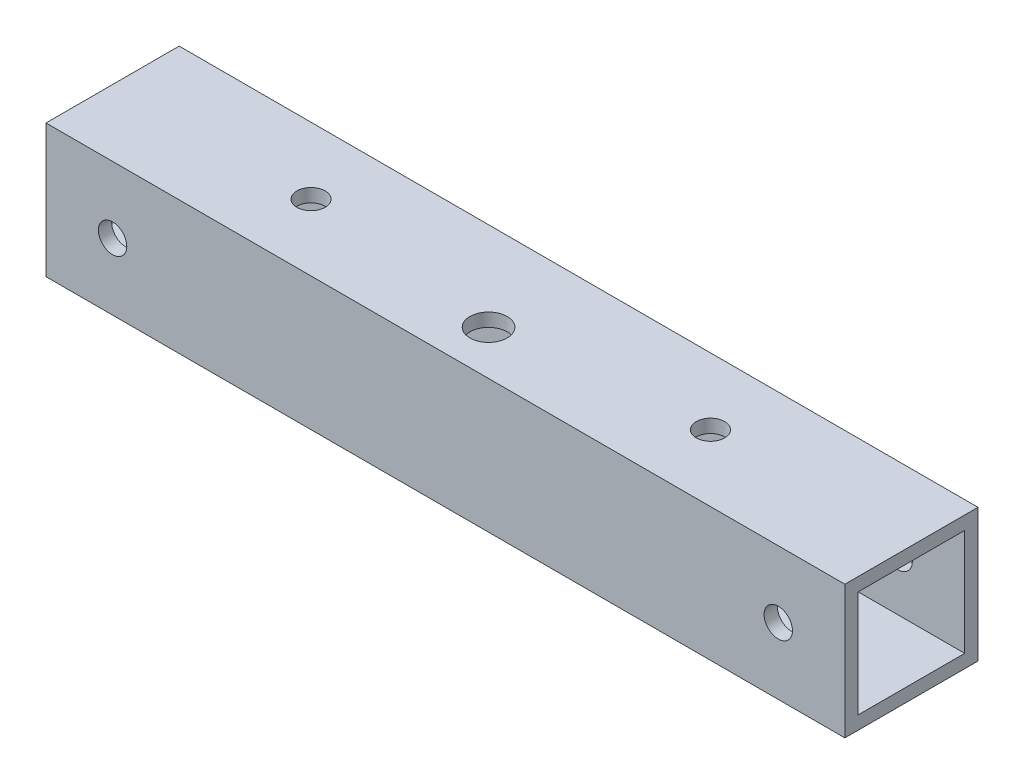
SolidWorks part; units mm, degrees
ref_plane "Front" through (0, 0, 0) normal (0, 0, 1) x (1, 0, 0)
ref_plane "Top" through (0, 0, 0) normal (0, 1, 0) x (1, 0, 0)
ref_plane "Right" through (0, 0, 0) normal (1, 0, 0) x (0, 0, -1)
sketch "ｽｹｯﾁ1" plane through (0, 0, 0) normal (1, 0, 0) x (0, 0, -1)
  line L0 (-6, 6) -> (6, 6)
  line L1 (-7.5, 7.5) -> (7.5, 7.5)
  line L2 (-7.5, 7.5) -> (-7.5, -7.5)
  line L3 (-7.5, -7.5) -> (7.5, -7.5)
  line L4 (7.5, 7.5) -> (7.5, -7.5)
  line L5 (0, -7.5) -> (0, 7.5) construction
  line L6 (-7.5, 0) -> (7.5, 0) construction
  line L7 (6, 6) -> (6, -6)
  line L8 (-6, -6) -> (6, -6)
  line L9 (-6, 6) -> (-6, -6)
  point P0 (0, 0)
  dimension "D1" = 15
  dimension "D2" = 15
  dimension "D3" = 1.5
extrude "ﾎﾞｽ - 押し出し1" add sketch "ｽｹｯﾁ1" along normal blind 90
sketch "ｽｹｯﾁ2" plane through (0, 7.5, 0) normal (0, 1, 0) x (1, 0, 0)
  line L0 (90, -7.5) -> (0, -7.5) construction
  line L2 (90, 7.5) -> (0, 7.5) construction
  circle A0 centre (44.8605, -2.5019) radius 2.1
  circle A1 centre (22.3605, 0) radius 1.6
  circle A2 centre (67.3605, 0) radius 1.6
  point P0 (45, -7.5)
  dimension "D1" = 22.5
  dimension "D2" = 22.5
  dimension "D3" = 5
  dimension "D4" = 7.5
  dimension "D5" = 4.2
  dimension "D6" = 3.2
  dimension "D7" = 3.2
  dimension "D8" = 7.5
  dimension "D9" = 4.9981
extrude "ｶｯﾄ - 押し出し1" cut sketch "ｽｹｯﾁ2" against normal through all
sketch "ｽｹｯﾁ3" plane through (0, 0, 7.5) normal (0, 0, 1) x (1, 0, 0)
  line L0 (0, 7.5) -> (0, -7.5) construction
  line L1 (90, -7.5) -> (0, -7.5) construction
  circle A0 centre (7.5, 0) radius 1.6
  circle A1 centre (82.5, 0) radius 1.6
  dimension "D1" = 75
  dimension "D2" = 7.5
  dimension "D3" = 7.5
  dimension "D4" = 7.5
  dimension "D5" = 3.2
  dimension "D6" = 3.2
extrude "ｶｯﾄ - 押し出し2" cut sketch "ｽｹｯﾁ3" against normal through all
